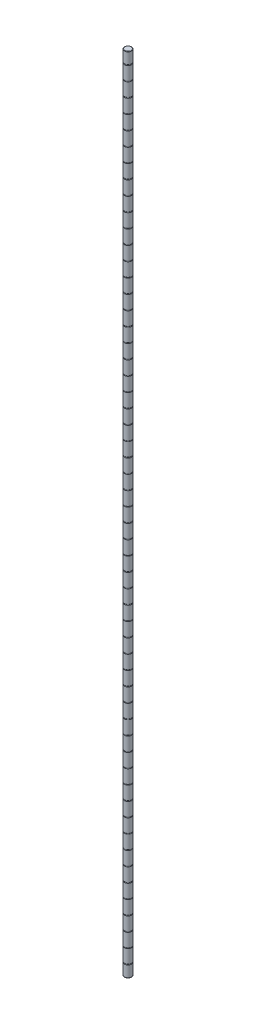
SolidWorks part; units mm, degrees
ref_plane "Alzado" through (0, 0, 0) normal (0, 0, 1) x (1, 0, 0)
ref_plane "Planta" through (0, 0, 0) normal (0, 1, 0) x (1, 0, 0)
ref_plane "Vista lateral" through (0, 0, 0) normal (1, 0, 0) x (0, 0, -1)
sketch "Croquis1" plane through (0, 0, 0) normal (0, 1, 0) x (1, 0, 0)
  circle A0 centre (0, 0) radius 7.5
  dimension "D1" = 15
extrude "Saliente-Extruir1" add sketch "Croquis1" along normal blind 1700
sketch "Croquis2" plane through (0, 0, 0) normal (0, 0, 1) x (1, 0, 0)
  line L1 (-7.5, 0) -> (7.5, 0) construction
  line L2 (0, 0) -> (0, 41.6369) construction
  line L3 (7.5, 0) -> (7.5, 1700) construction
  circle A0 centre (7.9, 25) radius 0.875
  dimension "D1" = 1.75
  dimension "D2" = 25
  dimension "D3" = 0.4
revolve "Cortar-Revolución1" cut sketch "Croquis2" angle 360 about L2
pattern_linear "MatrizL1" count 56 spacing 30 along (0, 1, 0) of "Cortar-Revolución1"
fillet "Redondeo1" radius 1 2 edges at (0, 1700, 7.5) (0, 0, 7.5)
hole_wizard "Refrentado para tornillo con cabeza plana de M51" positions "Croquis4" profile "Croquis3" counterbore size "M5" standard "DIN"
sketch "Croquis4" plane through (0, 0, 0) normal (0, -1, 0) x (-1, 0, 0)
  point P0 (0, 0)
sketch "Croquis3" plane through (0, 0, 0) normal (1, 0, 0) x (0, 0, -1)
  line L0 (0, 0) -> (0, 41.6524)
  line L1 (0, 41.6524) -> (2.75, 40)
  line L2 (2.75, 40) -> (2.75, 3.3)
  line L3 (2.75, 3.3) -> (5, 3.3)
  line L4 (5, 3.3) -> (5, 0)
  line L5 (5, 0) -> (0, 0)
  line L10 (0, 41.6524) -> (-2.75, 40) construction
  line L11 (0, -6.35) -> (0, 107.95) construction
  dimension "Diámetro de taladro" = 5.5
  dimension "Profundidad de taladro" = 40
  dimension "Diámetro de refrentado" = 10
  dimension "Profundidad de refrentado" = 3.3
  dimension "Ángulo de perforador" = 118
